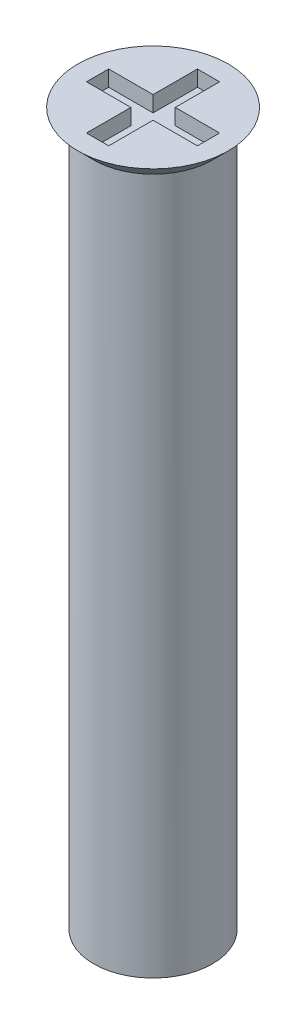
SolidWorks part; units mm, degrees
ref_plane "Front Plane" through (0, 0, 0) normal (0, 0, 1) x (1, 0, 0)
ref_plane "Top Plane" through (0, 0, 0) normal (0, 1, 0) x (1, 0, 0)
ref_plane "Right Plane" through (0, 0, 0) normal (1, 0, 0) x (0, 0, -1)
sketch "Sketch2" plane through (0, 0, 0) normal (0, 0, 1) x (1, 0, 0)
  line L0 (0, 0) -> (0, 9.3)
  line L1 (0, 9.3) -> (0.95, 9.3)
  line L2 (0.95, 9.3) -> (0.75, 9.1)
  line L3 (0.75, 9.1) -> (0.75, 0.3161)
  line L4 (0.75, 0.3161) -> (0, 0)
  dimension "D1" = 9.3
  dimension "D2" = 45
  dimension "D3" = 0.2
  dimension "D4" = 0.75
  dimension "D5" = 0.2828
revolve "Revolve1" add sketch "Sketch2" angle 360 about L0
sketch "Sketch3" plane through (0, 9.3, 0) normal (0, 1, 0) x (1, 0, 0)
  line L0 (0.14, 0.14) -> (0.7, 0.14)
  line L1 (-0.7, -0.14) -> (-0.14, -0.14)
  line L2 (-0.7, -0.14) -> (-0.7, 0.14)
  line L3 (-0.7, 0.14) -> (-0.14, 0.14)
  line L4 (0.7, -0.14) -> (0.7, 0.14)
  line L7 (-0.14, -0.7) -> (0.14, -0.7)
  line L8 (-0.14, -0.7) -> (-0.14, -0.14)
  line L9 (-0.14, 0.7) -> (0.14, 0.7)
  line L10 (0.14, -0.7) -> (0.14, -0.14)
  line L14 (-0.14, -0.14) -> (0.14, 0.14) construction
  line L15 (0.14, -0.14) -> (0.7, -0.14)
  line L16 (-0.14, 0.14) -> (0.14, -0.14) construction
  line L18 (0.14, 0.14) -> (0.14, 0.7)
  line L19 (-0.14, 0.14) -> (-0.14, 0.7)
  point P0 (0, 0)
  point P6 (0, 0)
  point P11 (0, 0)
  dimension "D1" = 1.4
  dimension "D2" = 1.4
  dimension "D3" = 0.28
  dimension "D4" = 0.28
extrude "Cut-Extrude1" cut sketch "Sketch3" against normal blind 0.2
